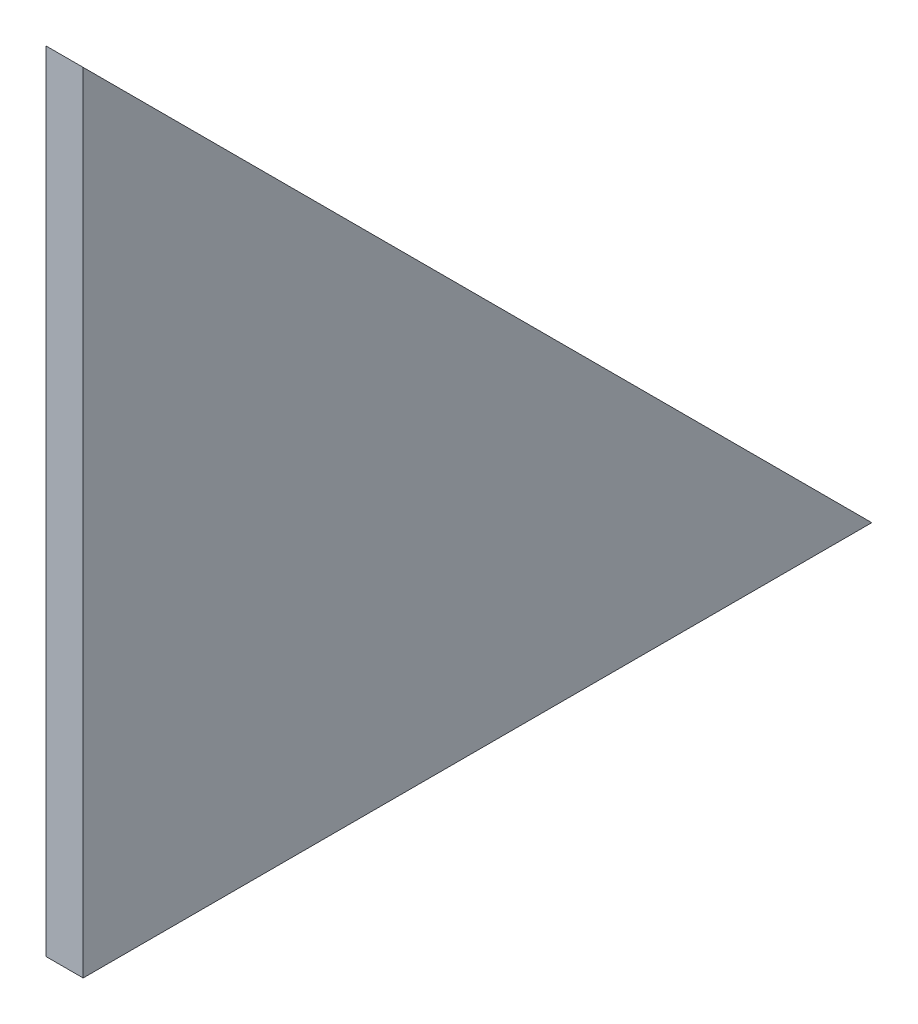
SolidWorks part; units mm, degrees
ref_plane "Front" through (0, 0, 0) normal (0, 0, 1) x (1, 0, 0)
ref_plane "Top" through (0, 0, 0) normal (0, 1, 0) x (1, 0, 0)
ref_plane "Right" through (0, 0, 0) normal (1, 0, 0) x (0, 0, -1)
sketch "Sketch1" plane through (0, 0, 0) normal (1, 0, 0) x (0, 0, -1)
  line L0 (0, 0) -> (0, 254)
  line L1 (0, 254) -> (254, 0)
  line L2 (254, 0) -> (0, 0)
  dimension "D1" = 254
  dimension "D2" = 45
extrude "Boss-Extrude1" add sketch "Sketch1" along normal blind 11.9062
